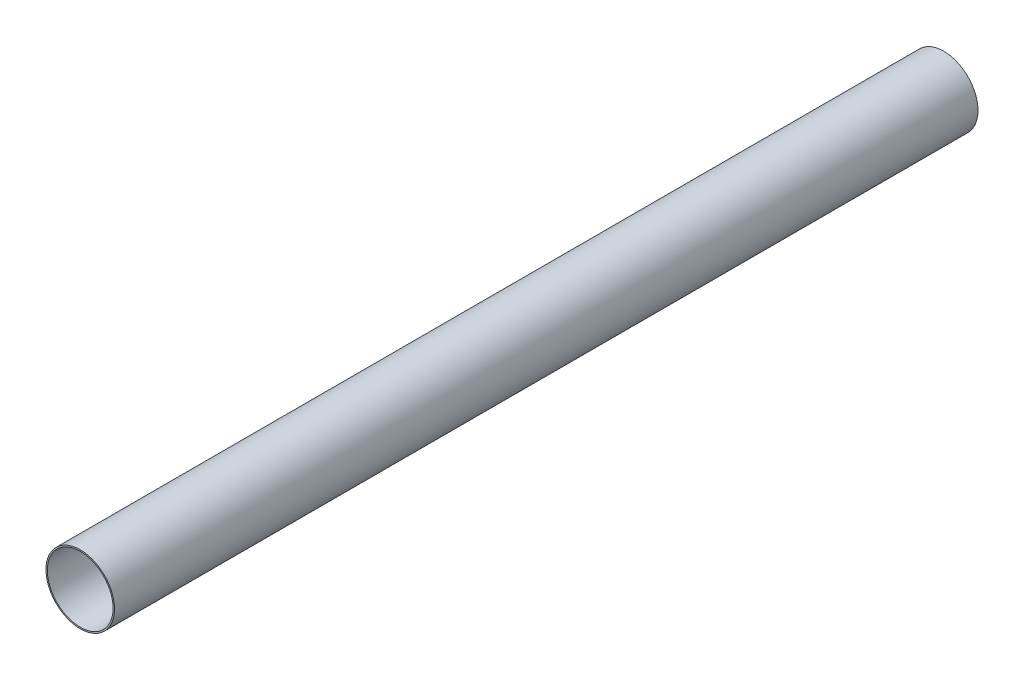
SolidWorks part; units mm, degrees
material "Fibra di Carbonio"
ref_plane "Front Plane" through (0, 0, 0) normal (0, 0, 1) x (1, 0, 0)
ref_plane "Top Plane" through (0, 0, 0) normal (0, 1, 0) x (1, 0, 0)
ref_plane "Right Plane" through (0, 0, 0) normal (1, 0, 0) x (0, 0, -1)
sketch "Sketch1" plane through (0, 0, 0) normal (0, 0, 1) x (1, 0, 0)
  circle A0 centre (0, 0) radius 72
  circle A1 centre (0, 0) radius 75
  dimension "D1" = 150
  dimension "D2" = 3
extrude "Boss-Extrude1" add sketch "Sketch1" along normal offset from surface (1891.222 mm away) 20
